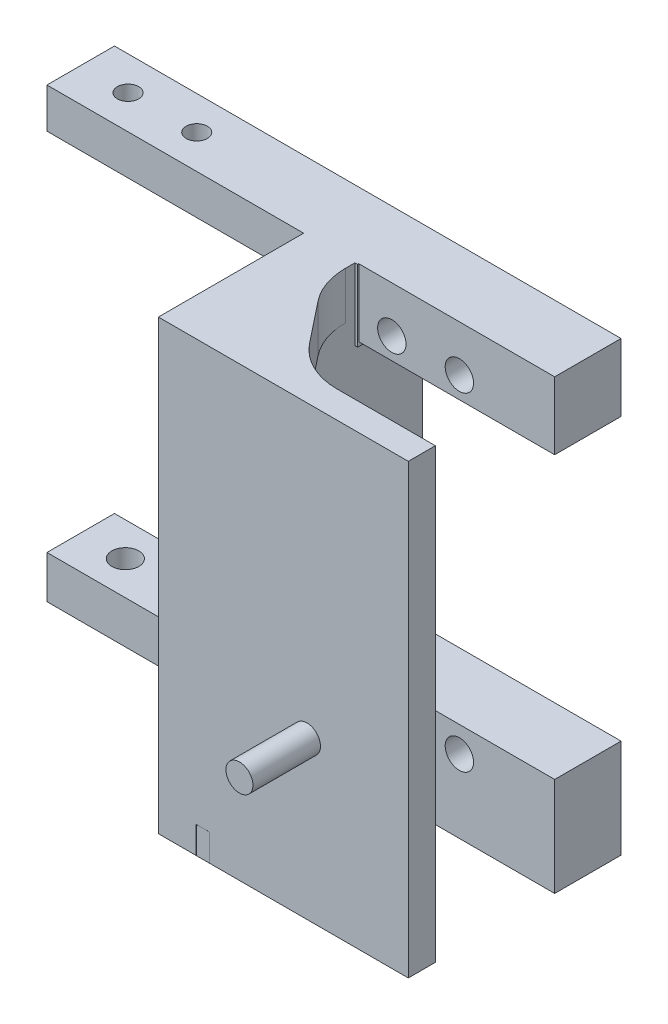
SolidWorks part; units mm, degrees
ref_plane "Front Plane" through (0, 0, 0) normal (0, 0, 1) x (1, 0, 0)
ref_plane "Top Plane" through (0, 0, 0) normal (0, 1, 0) x (1, 0, 0)
ref_plane "Right Plane" through (0, 0, 0) normal (1, 0, 0) x (0, 0, -1)
sketch "Sketch3" plane through (0, 0, 0) normal (0, 0, 1) x (1, 0, 0)
  line L0 (37.0075, -0.4854) -> (61.4075, -0.4854)
  line L1 (61.4075, -0.4854) -> (61.4075, -41.4854)
  line L2 (61.4075, -41.4854) -> (37.0075, -41.4854)
  line L3 (-8.5925, -46.3943) -> (-8.5925, -52.1104)
  line L4 (-8.5925, -52.1104) -> (66.4075, -52.1104)
  line L5 (66.4075, -52.1104) -> (66.4075, 10.1396)
  line L6 (66.4075, 10.1396) -> (-8.5925, 10.1396)
  line L7 (-8.5925, 10.1396) -> (-8.5925, 4.2177)
  line L8 (32.0075, 10.1396) -> (32.0075, -52.1104)
  line L11 (32.0075, -52.1104) -> (32.0075, 10.1396)
  line L12 (37.0075, 10.1396) -> (37.0075, -52.1104)
  line L13 (37.0075, -52.1104) -> (37.0075, 10.1396)
  line L14 (-8.5925, 4.2177) -> (32.0075, 4.2177)
  line L15 (32.0075, 4.2177) -> (-8.5925, 4.2177)
  line L16 (-8.5925, -46.3943) -> (32.0075, -46.3943)
  line L17 (32.0075, -46.3943) -> (-8.5925, -46.3943)
  line L18 (61.4075, -0.4854) -> (66.4075, -0.4854)
  line L19 (66.4075, -0.4854) -> (61.4075, -0.4854)
  line L20 (61.4075, -41.4854) -> (66.4075, -41.4854)
  line L21 (66.4075, -41.4854) -> (61.4075, -41.4854)
  dimension "D1" = 75
  dimension "D2" = 29.4
  dimension "D3" = 5
  dimension "D4" = 75
  dimension "D5" = 10.625
  dimension "D6" = 10.625
  dimension "D7" = 41
  dimension "D8" = 5
  dimension "D9" = 40.6
extrude "Boss-Extrude3" add sketch "Sketch3" along normal blind 29.5 contours L12 L6 L8 L11 L4 | L1 L20 L5 L18 | L20 L2 L12 L4 L5 | L0 L18 L5 L6 L12 | L7 L14 L8 L6 | L16 L3 L4 L8
sketch "Sketch4" plane through (0, -52.1104, 0) normal (0, -1, 0) x (1, 0, 0)
  line L0 (29.4075, 0) -> (29.4075, 29.5)
  line L1 (-8.5925, 0) -> (66.4075, 0) construction
  line L2 (-8.5925, 29.5) -> (66.4075, 29.5) construction
  line L3 (29.4075, 29.5) -> (29.4075, 0)
  line L4 (-8.5925, 29.5) -> (-8.5925, 0) construction
  line L5 (29.4075, 10) -> (-8.5925, 10)
  line L6 (-8.5925, 10) -> (29.4075, 10)
  dimension "D1" = 38
  dimension "D2" = 10
extrude "Cut-Extrude1" cut sketch "Sketch4" against normal blind 83
sketch "Sketch6" plane through (66.4075, 0, 0) normal (1, 0, 0) x (0, 0, -1)
  line L0 (-27.5, 10.1396) -> (-27.5, -52.1104)
  line L1 (-29.5, 10.1396) -> (0, 10.1396) construction
  line L2 (-29.5, -52.1104) -> (0, -52.1104) construction
  line L3 (-27.5, -52.1104) -> (-27.5, 10.1396)
  line L4 (-29.5, -52.1104) -> (-29.5, 10.1396) construction
  line M3 (0, 10.1396) -> (-29.5, 10.1396)
  line M4 (-29.5, 10.1396) -> (-29.5, -52.1104)
  line M5 (-29.5, -52.1104) -> (0, -52.1104)
  dimension "D1" = 2
extrude "Boss-Extrude4" add sketch "Sketch6" against normal blind 30 contours L0 M3 M4 M5
sketch "Sketch9" plane through (0, -52.1104, 0) normal (0, -1, 0) x (-1, 0, 0)
  line L0 (-32.0075, -10) -> (-66.4075, -10)
  line L1 (-66.4075, -29.5) -> (-66.4075, 0) construction
  line L2 (-66.4075, -10) -> (-32.0075, -10)
  line L3 (-37.0075, -10) -> (-37.0075, -27.5)
  line L4 (-37.0075, -27.5) -> (-61.4075, -27.5)
  line L5 (-61.4075, -27.5) -> (-61.4075, -10)
  line L6 (-32.0075, -10) -> (-32.0075, -29.5) construction
  line L7 (-29.4075, -29.5) -> (-66.4075, -29.5) construction
  dimension "D1" = 5
  dimension "D2" = 5
  dimension "D3" = 2
extrude "Cut-Extrude3" cut sketch "Sketch9" against normal blind 77 and the other way through all contours L5 L4 L3 L2
sketch "Sketch10" plane through (0, 0, 29.5) normal (0, 0, 1) x (1, 0, 0)
  line L0 (66.4075, -52.1104) -> (66.4075, 10.1396) construction
  line L1 (29.4075, -52.1104) -> (66.4075, -52.1104) construction
  circle A0 centre (51.4075, -32.9004) radius 2
  dimension "D1" = 4
  dimension "D2" = 15
  dimension "D3" = 19.21
extrude "Boss-Extrude5" add sketch "Sketch10" along normal blind 12
sketch "Sketch11" plane through (66.4075, 0, 0) normal (1, 0, 0) x (0, 0, -1)
  line L0 (0, -41.4854) -> (-9.8295, -41.4854)
  line L1 (-24.463, -42.1104) -> (-24.463, 0)
  line L3 (-9.8295, 10.1396) -> (-9.8295, 0.1396)
  line L4 (-29.5, 10.1396) -> (0, 10.1396) construction
  line L5 (-9.8295, -41.4854) -> (-9.8295, -52.1104)
  line L6 (-29.5, -52.1104) -> (0, -52.1104) construction
  line L7 (-9.8295, -52.1104) -> (-24.463, -52.1104)
  line L8 (-24.463, -52.1104) -> (-24.463, -42.1104)
  line L9 (-24.463, 0) -> (-24.463, 10.1396)
  line L10 (-24.463, 10.1396) -> (-9.8295, 10.1396)
  line L12 (-9.8295, 0.1396) -> (0, 0.1396)
  line L13 (0, -52.1104) -> (0, 10.1396) construction
  line L14 (0, 0.1396) -> (0, -41.4854)
  dimension "D1" = 10
extrude "Cut-Extrude4" cut sketch "Sketch11" against normal blind 29
sketch "Sketch12" plane through (0, 10.1396, 0) normal (0, 1, 0) x (1, 0, 0)
  line L0 (61.4075, -27.5) -> (66.4075, -27.5)
  line L1 (66.4075, -29.5) -> (66.4075, -24.463) construction
  line L2 (66.4075, -27.5) -> (61.4075, -27.5)
  line M1 (66.4075, -29.5) -> (66.4075, -24.463)
  line M2 (66.4075, -24.463) -> (61.4075, -24.463)
  line M3 (61.4075, -24.463) -> (61.4075, -27.5)
extrude "Cut-Extrude5" cut sketch "Sketch12" against normal blind 66 contours L0 M3 M1 M2
sketch "Sketch13" plane through (0, 10.1396, 0) normal (0, 1, 0) x (1, 0, 0)
  line L0 (-8.5925, -5) -> (66.4075, -4.9148) construction
  line L1 (-8.5925, -10) -> (-8.5925, 0) construction
  line L2 (66.4075, -9.8295) -> (66.4075, 0) construction
  circle A0 centre (-1.5925, -4.992) radius 1.575
  circle A1 centre (8.5675, -4.9805) radius 1.575
  dimension "D1" = 3.15
  dimension "D2" = 3.15
  dimension "D3" = 10.16
  dimension "D4" = 7
extrude "Cut-Extrude6" cut sketch "Sketch13" against normal blind 20
sketch "Sketch14" plane through (0, 10.1396, 0) normal (0, 1, 0) x (1, 0, 0)
  line L0 (47.0075, -27.5) -> (37.0075, -14.8946)
  line L1 (37.0075, -27.5) -> (37.0075, -10) construction
  line L2 (37.0075, -14.8946) -> (37.0075, -27.5)
  line L3 (37.0075, -27.5) -> (47.0075, -27.5)
extrude "Boss-Extrude6" add sketch "Sketch14" against normal blind 7
fillet "Fillet1" radius 10 2 edges at (37.0075, 6.6396, 14.8946) (47.0075, 6.6396, 27.5)
sketch "Sketch15" plane through (0, 0, 0) normal (0, 0, -1) x (-1, 0, 0)
  line L0 (-37.0075, -41.4854) -> (-66.4075, -41.4854) construction
  line L1 (-37.0075, -0.4854) -> (-37.4075, -0.4854) construction
  line L2 (-32.0075, 4.2177) -> (-32.0075, -46.3943) construction
  circle A0 centre (-42.2975, -45.2854) radius 2.1
  circle A1 centre (-52.2975, -45.2854) radius 2.1
  circle A2 centre (-42.2975, 3.3146) radius 2.1
  circle A3 centre (-52.2975, 3.3146) radius 2.1
  dimension "D3" = 4.2
  dimension "D4" = 4.2
  dimension "D8" = 4.2
  dimension "D9" = 4.2
  dimension "D1" = 3.8
  dimension "D2" = 3.8
  dimension "D5" = 10
  dimension "D6" = 3.8
  dimension "D7" = 3.8
  dimension "D10" = 10
  dimension "D11" = 10.29
  dimension "D12" = 10.29
extrude "Cut-Extrude7" cut sketch "Sketch15" against normal blind 13
sketch "Sketch16" plane through (0, 0, 29.5) normal (0, 0, 1) x (1, 0, 0)
  line L0 (66.4075, 10.1396) -> (66.4075, -52.1104)
  line L1 (66.4075, 10.1396) -> (29.4075, 10.1396)
  line L2 (66.4075, -52.1104) -> (29.4075, -52.1104)
  line L3 (29.4075, 10.1396) -> (29.4075, -52.1104)
  line L4 (29.4075, -52.1104) -> (29.4075, -46.3943) construction
extrude "Boss-Extrude7" add sketch "Sketch16" along normal blind 2
sketch "Sketch17" plane through (0, -52.1104, 0) normal (0, -1, 0) x (1, 0, 0)
  line L1 (66.4075, 0) -> (-8.5925, 0)
  line L2 (66.4075, 0) -> (66.4075, 10)
  line L3 (66.4075, 10) -> (-8.5925, 10)
  line L4 (-8.5925, 0) -> (-8.5925, 10)
  line L5 (66.4075, 27.5) -> (29.4075, 27.5)
  line L6 (66.4075, 27.5) -> (66.4075, 31.5)
  line L7 (66.4075, 31.5) -> (29.4075, 31.5)
  line L8 (29.4075, 27.5) -> (29.4075, 31.5)
  line L9 (37.0075, 31.5035) -> (35.0757, 31.5035)
  line L10 (37.0075, 31.5035) -> (37.0075, 10)
  line L11 (37.0075, 10) -> (35.0757, 10)
  line L12 (35.0757, 31.5035) -> (35.0757, 10)
  line M13 (37.0075, 27.5) -> (66.4075, 27.5)
  line M14 (66.4075, 27.5) -> (66.4075, 31.5)
  line M15 (66.4075, 31.5) -> (29.4075, 31.5)
  line M16 (29.4075, 31.5) -> (29.4075, 10)
  line M17 (29.4075, 10) -> (-8.5925, 10)
  line M18 (-8.5925, 10) -> (-8.5925, 0)
  line M19 (-8.5925, 0) -> (66.4075, 0)
  line M20 (66.4075, 0) -> (66.4075, 9.8295)
  line M21 (66.4075, 9.8295) -> (37.4075, 9.8295)
  line M22 (37.0075, 10) -> (37.0075, 27.5)
extrude "Boss-Extrude8" add sketch "Sketch17" along normal blind 4 contours L3 M22 M17 M18 M19 M20 M21 | L9 L12 L7 L10 M17 M16 | L5 L3 M22 M16 | L10 L7 L5 M16 | L10 M15 M13 M14
sketch "Sketch19" plane through (0, 0, 0) normal (0, 0, -1) x (-1, 0, 0)
  line L0 (8.5925, -46.3943) -> (8.5925, -56.1104) construction
  line L1 (-32.0075, -46.3943) -> (8.5925, -46.3943)
  line L2 (-32.0075, -46.3943) -> (-32.0075, -49.7981)
  line L3 (-32.0075, -49.7981) -> (8.5925, -49.7981)
  line L4 (8.5925, -46.3943) -> (8.5925, -49.7981)
extrude "Cut-Extrude8" cut sketch "Sketch19" against normal through all
sketch "Sketch20" plane through (0, 10.1396, 0) normal (0, 1, 0) x (1, 0, 0)
  line L0 (29.4075, -10) -> (-8.5925, -10) construction
  line L1 (29.4075, -31.5) -> (34.9648, -31.5)
  line L2 (29.4075, -31.5) -> (29.4075, -10)
  line L3 (29.4075, -10) -> (34.9648, -10)
  line L4 (34.9648, -31.5) -> (34.9648, -10)
extrude "Boss-Extrude9" add sketch "Sketch20" against normal up to surface (66.25 mm away) up to face at (38.6744, -56.1104, 17.1904)
sketch "Sketch22" plane through (0, -56.1104, 0) normal (0, -1, 0) x (1, 0, 0)
  line L16 (37.0075, 31.5035) -> (35.0757, 31.5035)
  line L17 (35.0757, 31.5035) -> (35.0757, 10)
  line L18 (35.0757, 10) -> (34.9648, 10)
  line L19 (34.9648, 10) -> (34.9648, 31.5)
  line L20 (34.9648, 31.5) -> (29.4075, 31.5)
  line L21 (29.4075, 31.5) -> (29.4075, 10)
  line L22 (29.4075, 10) -> (-8.5925, 10)
  line L23 (-8.5925, 10) -> (-8.5925, 0)
  line L24 (-8.5925, 0) -> (66.4075, 0)
  line L25 (66.4075, 0) -> (66.4075, 9.8295)
  line L26 (66.4075, 9.8295) -> (37.4075, 9.8295)
  line L27 (37.0075, 10) -> (37.0075, 27.5)
  line L28 (37.0075, 27.5) -> (66.4075, 27.5)
  line L29 (66.4075, 27.5) -> (66.4075, 31.5)
  line L30 (66.4075, 31.5) -> (37.0075, 31.5)
  line L31 (37.0075, 31.5) -> (37.0075, 31.5035)
  line L32 (37.0075, 31.5035) -> (35.0757, 31.5035)
  line L33 (35.0757, 31.5035) -> (35.0757, 10)
  line L34 (35.0757, 10) -> (34.9648, 10)
  line L35 (34.9648, 10) -> (34.9648, 31.5)
  line L36 (34.9648, 31.5) -> (29.4075, 31.5)
  line L37 (29.4075, 31.5) -> (29.4075, 10)
  line L38 (29.4075, 10) -> (-8.5925, 10)
  line L39 (-8.5925, 10) -> (-8.5925, 0)
  line L40 (-8.5925, 0) -> (66.4075, 0)
  line L41 (66.4075, 0) -> (66.4075, 9.8295)
  line L42 (66.4075, 9.8295) -> (37.4075, 9.8295)
  line L43 (37.0075, 10) -> (37.0075, 27.5)
  line L44 (37.0075, 27.5) -> (66.4075, 27.5)
  line L45 (66.4075, 27.5) -> (66.4075, 31.5)
  line L46 (66.4075, 31.5) -> (37.0075, 31.5)
  line L47 (37.0075, 31.5) -> (37.0075, 31.5035)
  line L50 (37.4075, 9.8295) -> (37.4075, 10)
  line L51 (37.4075, 9.8295) -> (37.4075, 10)
  line L52 (37.4075, 10) -> (37.0075, 10)
  line L53 (37.4075, 10) -> (37.0075, 10)
  circle A0 centre (-1.9925, 4.992) radius 2 construction
  circle A1 centre (-1.9925, 4.992) radius 2
  dimension "D1" = 0
extrude "Cut-Extrude11" cut sketch "Sketch22" against normal blind 12 contours A1
